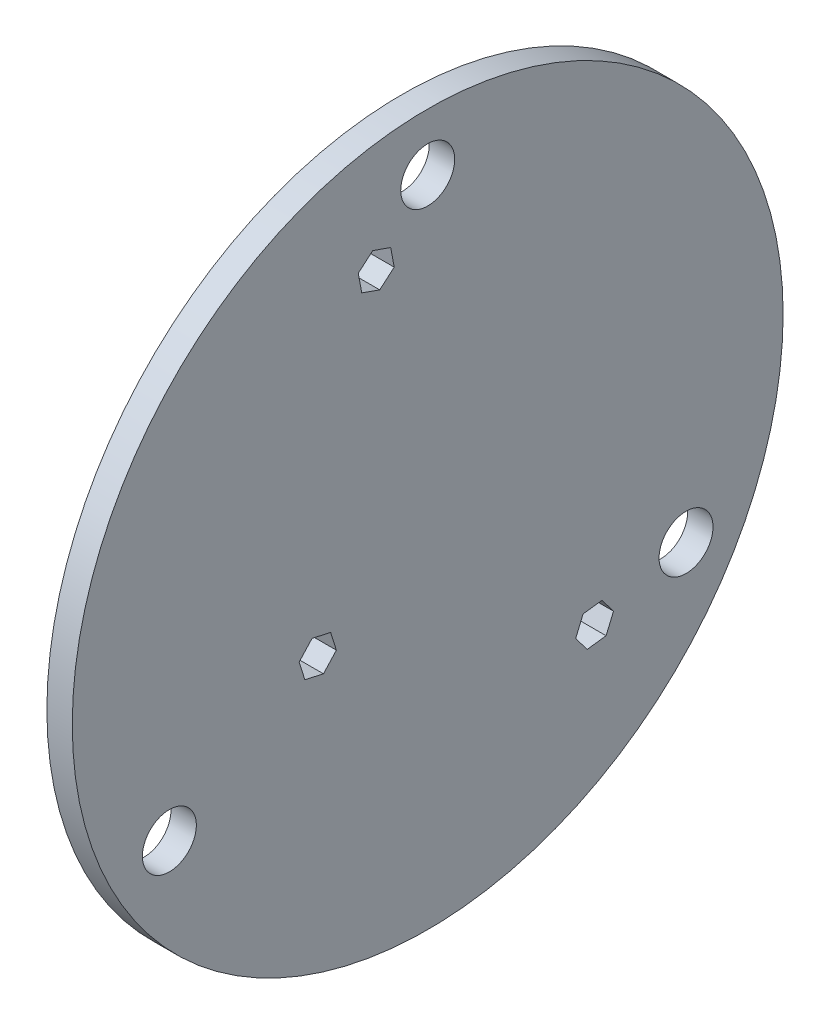
SolidWorks part; units mm, degrees
ref_plane "Ebene vorne" through (0, 0, 0) normal (0, 0, 1) x (1, 0, 0)
ref_plane "Ebene oben" through (0, 0, 0) normal (0, 1, 0) x (1, 0, 0)
ref_plane "Ebene rechts" through (0, 0, 0) normal (1, 0, 0) x (0, 0, -1)
sketch "Sketch1" plane through (0, 0, 0) normal (1, 0, 0) x (0, 0, -1)
  circle A0 centre (0, 0) radius 56
  dimension "D1" = 112
extrude "Boss-Extrude1" add sketch "Sketch1" along normal blind 4
sketch "Sketch2" plane through (0, 0, 0) normal (-1, 0, 0) x (0, 0, 1)
  circle A1 centre (0, 47) radius 4.25
  circle A2 centre (40.7032, -23.5) radius 4.25
  circle A3 centre (-40.7032, -23.5) radius 4.25
  point P9 (0, 0)
  point P13 (0, 0)
  dimension "D4" = 3
  dimension "D2" = 47
extrude "Cut-Extrude1" cut sketch "Sketch2" against normal through all
sketch "Sketch3" [suppressed] plane through (0, 0, 0) normal (-1, 0, 0) x (0, 0, 1)
  line L0 (-30, -47.2864) -> (-30, -36.2864)
  line L1 (0, 56) -> (0, -56) construction
  line L2 (30, -47.2864) -> (30, -36.2864)
  line L3 (-30, -36.2864) -> (30, -36.2864)
  circle A0 centre (0, 0) radius 56 construction
  arc A2 (-30, -47.2864) -> (30, -47.2864) centre (0, 0) ccw
  dimension "D1" = 11
  dimension "D2" = 60
extrude "Cut-Extrude2" [suppressed] cut sketch "Sketch3" against normal through all
sketch "Sketch4" plane through (4, 0, 0) normal (1, 0, 0) x (0, 0, -1)
  line L25 (27.4594, -24.776) -> (24.4806, -25.1504)
  line L26 (24.4806, -25.1504) -> (23.3154, -27.9173)
  line L27 (23.3154, -27.9173) -> (25.1291, -30.3098)
  line L28 (25.1291, -30.3098) -> (28.1078, -29.9355)
  line L29 (28.1078, -29.9355) -> (29.273, -27.1686)
  line L30 (29.273, -27.1686) -> (27.4594, -24.776)
  line L31 (-10.3888, 36.0911) -> (-7.5579, 35.0915)
  line L32 (-7.5579, 35.0915) -> (-5.2768, 37.0434)
  line L33 (-5.2768, 37.0434) -> (-5.8266, 39.9948)
  line L34 (-5.8266, 39.9948) -> (-8.6575, 40.9944)
  line L35 (-8.6575, 40.9944) -> (-10.9386, 39.0425)
  line L36 (-10.9386, 39.0425) -> (-10.3888, 36.0911)
  line L37 (-16.4245, -12.8654) -> (-14.391, -10.6567)
  line L38 (-14.391, -10.6567) -> (-15.287, -7.7913)
  line L39 (-15.287, -7.7913) -> (-18.2166, -7.1346)
  line L40 (-18.2166, -7.1346) -> (-20.25, -9.3433)
  line L41 (-20.25, -9.3433) -> (-19.354, -12.2087)
  line L42 (-19.354, -12.2087) -> (-16.4245, -12.8654)
  circle A0 centre (26.2942, -27.5429) radius 2.6 construction
  circle A2 centre (-8.1077, 38.0429) radius 2.6 construction
  circle A3 centre (-17.3205, -10) radius 2.6 construction
  point P0 (0, 0)
  dimension "D1" = 5.2
  dimension "D2" = 5.2
extrude "Cut-Extrude3" cut sketch "Sketch4" against normal through all
